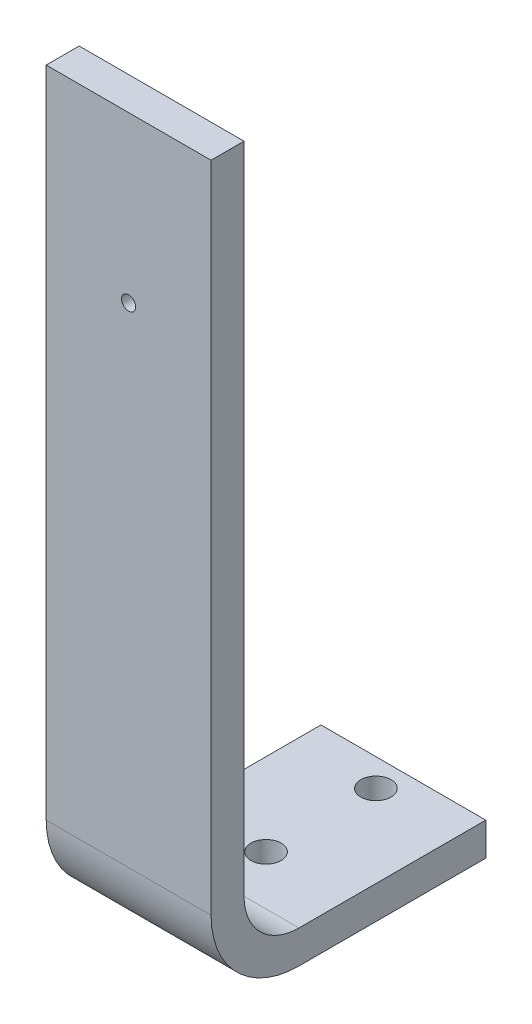
SolidWorks part; units mm, degrees
ref_plane "Front Plane" through (0, 0, 0) normal (0, 0, 1) x (1, 0, 0)
ref_plane "Top Plane" through (0, 0, 0) normal (0, 1, 0) x (1, 0, 0)
ref_plane "Right Plane" through (0, 0, 0) normal (1, 0, 0) x (0, 0, -1)
sketch "Sketch1" plane through (0, 0, 0) normal (1, 0, 0) x (0, 0, -1)
  line L0 (0, 0) -> (50, 0)
  line L1 (0, 0) -> (0, 135)
  line L2 (6, 135) -> (6, 6)
  line L3 (6, 6) -> (50, 6)
  line L4 (0, 135) -> (6, 135)
  line L5 (50, 6) -> (50, 0)
  dimension "D1" = 6
  dimension "D2" = 6
  dimension "D3" = 50
  dimension "D4" = 135
extrude "Boss-Extrude1" add sketch "Sketch1" along normal blind 30
fillet "Fillet1" radius 10 1 edges at (15, 6, -6)
fillet "Fillet2" radius 16 1 edges at (15, 0, 0)
hole_wizard "M5 Clearance Hole1" positions "Sketch2" profile "Sketch3" hole size "M5" standard "ANSI Metric" end condition through all
sketch "Sketch2" plane through (0, 6, 0) normal (0, 1, 0) x (1, 0, 0)
  line L0 (15, 50) -> (15, 16) construction
  line L1 (30, 50) -> (0, 50) construction
  line L2 (0, 16) -> (30, 16) construction
  point P0 (15, 45)
  point P2 (15, 25)
  point P14 (0, 0)
  point P15 (0, 0)
  dimension "D1" = 20
  dimension "D2" = 5
sketch "Sketch3" plane through (15, 6, -45) normal (1, 0, 0) x (0, 0, 1)
  line L0 (0, 0) -> (0, 6)
  line L1 (0, 6) -> (2.75, 6)
  line L2 (2.75, 6) -> (2.75, 0)
  line L5 (2.75, 0) -> (0, 0)
  line L11 (0, -6.35) -> (0, 107.95) construction
  dimension "Thru Hole Dia." = 5.5
  dimension "Thru Hole Depth" = 6
hole_wizard "#5-40 Tapped Hole1" positions "Sketch4" profile "Sketch5" tap size "#5-40" standard "ANSI Inch" end condition through all
sketch "Sketch4" plane through (0, 0, 0) normal (0, 0, 1) x (1, 0, 0)
  line L0 (15, 135) -> (15, 16) construction
  line L1 (30, 135) -> (0, 135) construction
  line L2 (0, 16) -> (30, 16) construction
  point P0 (15, 105)
  point P12 (0, 0)
  dimension "D1" = 30
sketch "Sketch5" plane through (15, 105, 0) normal (1, 0, 0) x (0, -1, 0)
  line L0 (0, 0) -> (0, 50)
  line L1 (0, 50) -> (1.289, 50)
  line L2 (1.289, 50) -> (1.289, 0)
  line L5 (1.289, 0) -> (0, 0)
  line L11 (0, -6.35) -> (0, 107.95) construction
  dimension "Thru Tap Drill Dia." = 2.5781
  dimension "Thru Tap Drill Depth" = 50
cosmetic thread "Hole Thread1"
